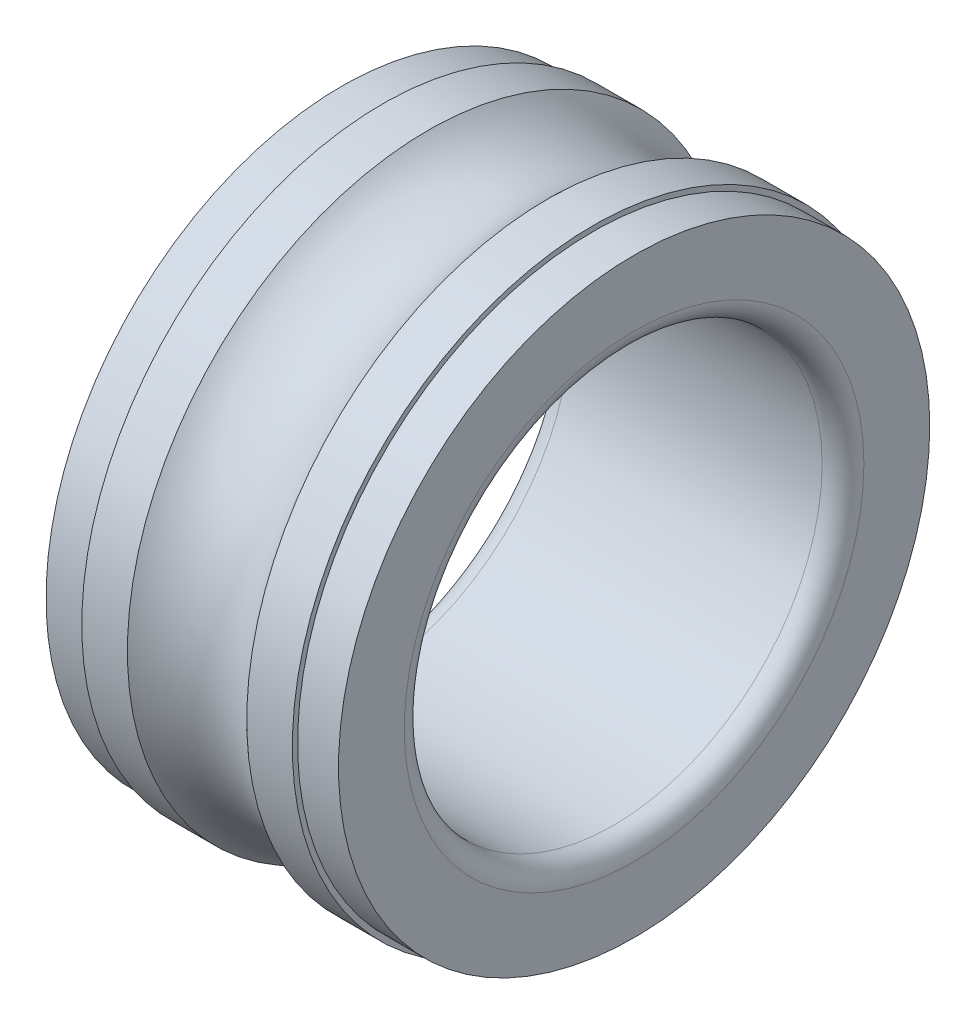
SolidWorks part; units mm, degrees
ref_plane "Front Plane" through (0, 0, 0) normal (0, 0, 1) x (1, 0, 0)
ref_plane "Top Plane" through (0, 0, 0) normal (0, 1, 0) x (1, 0, 0)
ref_plane "Right Plane" through (0, 0, 0) normal (1, 0, 0) x (0, 0, -1)
sketch "Sketch1" plane through (0, 0, 0) normal (0, 0, 1) x (1, 0, 0)
  line L0 (0, 10) -> (0, 0) construction
  line L1 (-6, 10) -> (6, 10)
  line L2 (0, 0) -> (-11.4383, 0) construction
  line L3 (5.04, 14.4) -> (5.04, 14.15)
  line L4 (-7, 11) -> (-7, 14.15)
  line L5 (-5.04, 14.4) -> (-2.8566, 14.4)
  line L6 (7, 14.15) -> (7, 11)
  line L7 (-6, 23.5) -> (6, 23.5) construction
  line L8 (7, 22.5) -> (7, 20.545) construction
  line L9 (5.0429, 20.295) -> (2.534, 20.295) construction
  line L10 (-7, 20.545) -> (-7, 22.5) construction
  line L11 (0, 17.2) -> (7, 17.2) construction
  line L12 (7, 17.2) -> (7, 20.295) construction
  line L13 (2.8566, 14.4) -> (5.04, 14.4)
  line L14 (-2.534, 20.295) -> (-5.0429, 20.295) construction
  line L15 (7, 17.2) -> (7, 14.4) construction
  line L16 (-7, 20.545) -> (-6.5, 20.545) construction
  line L17 (6.5, 20.545) -> (7, 20.545) construction
  line L18 (5.0429, 20.295) -> (7, 20.295) construction
  line L20 (7, 20.545) -> (7, 20.295) construction
  line L21 (-5.0429, 20.295) -> (-5.7929, 20.295) construction
  line L24 (5.04, 14.15) -> (7, 14.15)
  line L25 (5.04, 14.4) -> (7, 14.4) construction
  line L26 (-7, 14.15) -> (-5.04, 14.15)
  line L27 (-5.04, 14.15) -> (-5.04, 14.4)
  arc A0 (6, 10) -> (7, 11) centre (6, 11) ccw
  arc A1 (-7, 11) -> (-6, 10) centre (-6, 11) ccw
  arc A2 (6, 23.5) -> (7, 22.5) centre (6, 22.5) cw construction
  arc A3 (-6, 23.5) -> (-7, 22.5) centre (-6, 22.5) ccw construction
  arc A4 (-2.8566, 14.4) -> (2.8566, 14.4) centre (0, 17.2) ccw
  arc A5 (2.534, 20.295) -> (-2.534, 20.295) centre (0, 17.2) ccw construction
  arc A7 (6.5, 20.545) -> (5.0429, 20.295) centre (5.7929, 20.295) ccw construction
  arc A8 (-6.5, 20.545) -> (-5.0429, 20.295) centre (-5.7929, 20.295) cw construction
  dimension "D6" = 1
  dimension "D7" = 8
  dimension "D10" = 0.75
  dimension "D11" = 4
  dimension "D15" = 0.75
  dimension "D8" = 4
  dimension "D24" = 6.145
  dimension "D25" = 20.295
  dimension "D2" = 10
  dimension "D3" = 14.4
  dimension "D4" = 20.295
  dimension "D5" = 23.5
  dimension "D9" = 2.8
  dimension "D12" = 7
  dimension "D13" = 0.25
  dimension "D14" = 0.5
  dimension "D16" = 0.5
  dimension "D17" = 14
  dimension "D18" = 17.2
  dimension "D19" = 1.96
  dimension "D20" = 0.25
  dimension "D21" = 1.9571
  dimension "D22" = 3.095
  dimension "D23" = 1.96
revolve "Revolve1" add sketch "Sketch1" angle 360 about L2
